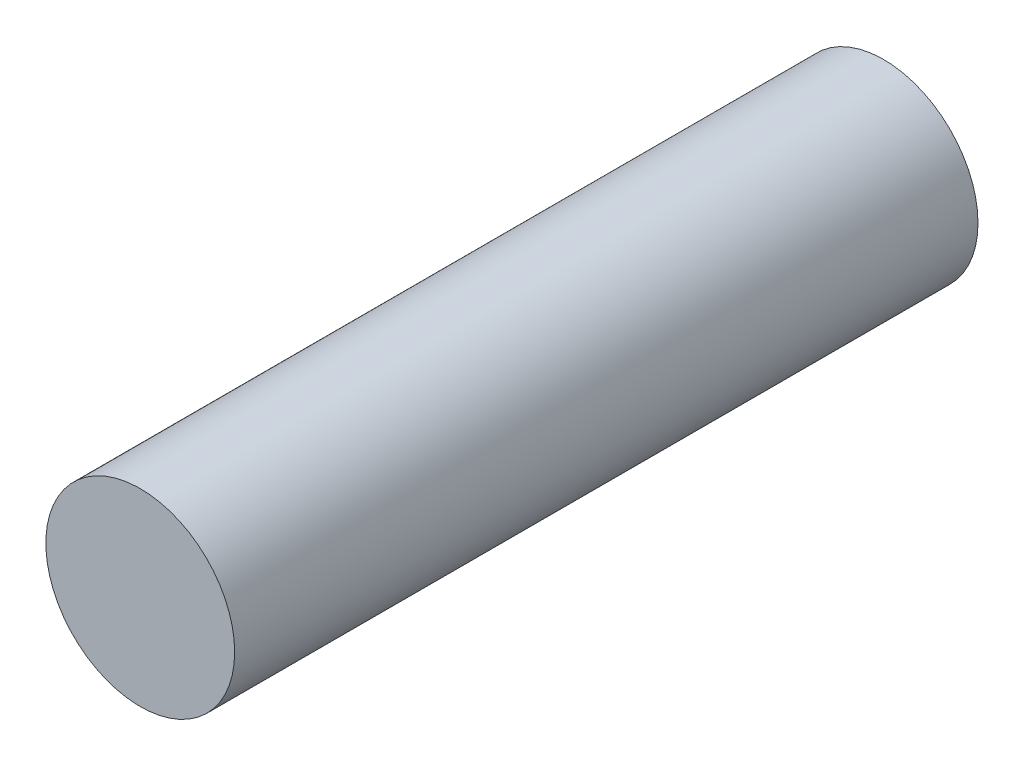
SolidWorks part; units mm, degrees
ref_plane "Front Plane" through (0, 0, 0) normal (0, 0, 1) x (1, 0, 0)
ref_plane "Top Plane" through (0, 0, 0) normal (0, 1, 0) x (1, 0, 0)
ref_plane "Right Plane" through (0, 0, 0) normal (1, 0, 0) x (0, 0, -1)
sketch "Sketch1" plane through (0, 0, 0) normal (0, 0, 1) x (1, 0, 0)
  circle A0 centre (0, 0) radius 6.35
  dimension "D1" = 12.7
extrude "Boss-Extrude1" add sketch "Sketch1" along normal mid plane 50 contours A0
